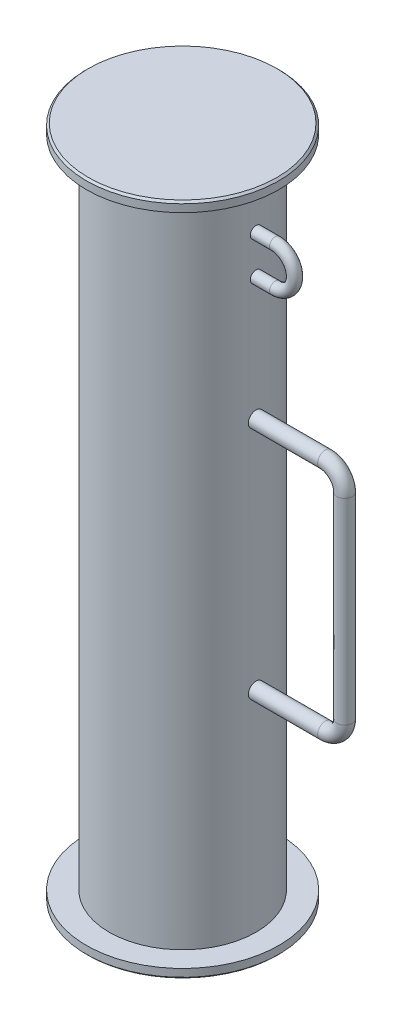
SolidWorks part; units mm, degrees
material "SGP"
ref_plane "前基準面" through (0, 0, 0) normal (0, 0, 1) x (1, 0, 0)
ref_plane "上基準面" through (0, 0, 0) normal (0, 1, 0) x (1, 0, 0)
ref_plane "右基準面" through (0, 0, 0) normal (1, 0, 0) x (0, 0, -1)
sketch "骨架1" plane through (0, 0, 0) normal (0, 1, 0) x (1, 0, 0)
  circle A0 centre (0, 0) radius 38.15
  circle A1 centre (0, 0) radius 50
  circle A2 centre (0, 0) radius 33.95
  dimension "D1" = 100
  dimension "D2" = 76.3
  dimension "D3" = 67.9
sketch "骨架2" plane through (0, 0, 0) normal (0, 0, 1) x (1, 0, 0)
  line L0 (0, 0) -> (0, -398.6797) construction
  point P3 (0, -5)
  point P4 (0, -345)
  point P5 (0, -350)
  dimension "D1" = 5
  dimension "D2" = 340
  dimension "D3" = 5
sketch "草圖1" plane through (0, 0, 0) normal (0, 1, 0) x (1, 0, 0)
  circle A0 centre (0, 0) radius 50
  circle A3 centre (0, 0) radius 50 construction
extrude "填料-伸長1" add sketch "草圖1" against normal up to vertex (5 mm away) up to point (0, -5, 0)
sketch "草圖2" plane through (0, -5, 0) normal (0, -1, 0) x (1, 0, 0)
  circle A0 centre (0, 0) radius 38.15
  circle A1 centre (0, 0) radius 33.95
  circle A2 centre (0, 0) radius 38.15 construction
  circle A3 centre (0, 0) radius 33.95 construction
extrude "填料-伸長2" add sketch "草圖2" along normal up to vertex (340 mm away) up to point (0, -345, 0)
sketch "草圖3" plane through (0, -345, 0) normal (0, -1, 0) x (1, 0, 0)
  circle A0 centre (0, 0) radius 50
  circle A1 centre (0, 0) radius 50 construction
extrude "填料-伸長3" add sketch "草圖3" along normal up to vertex (5 mm away) up to point (0, -350, 0)
ref_plane "平面1" through (38.15, 0, 0) normal (1, 0, 0) x (0, 0, -1)
sketch "草圖4" plane through (38.15, 0, 0) normal (1, 0, 0) x (0, 0, -1)
  line L0 (-50, -350) -> (50, -350) construction
  circle A0 centre (0, -114) radius 4
  dimension "D1" = 8
  dimension "D2" = 236
sketch "草圖5" plane through (0, 0, 0) normal (0, 0, 1) x (1, 0, 0)
  line L0 (38.15, -114) -> (74.15, -114)
  line L1 (38.15, -55) -> (38.15, 55) construction
  line L2 (84.15, -124) -> (84.15, -226)
  line L3 (74.15, -236) -> (38.15, -236)
  line L5 (-50, -350) -> (50, -350) construction
  arc A0 (84.15, -226) -> (74.15, -236) centre (74.15, -226) cw
  arc A1 (74.15, -114) -> (84.15, -124) centre (74.15, -124) cw
  point P10 (84.15, -236)
  point P13 (84.15, -114)
  dimension "D4" = 10
  dimension "D1" = 114
  dimension "D2" = 122
  dimension "D3" = 46
sweep "掃出1" add profiles "草圖4" path "草圖5"
chamfer "導角1" distance 1 angle 45 2 edges at (0, -350, -50) (0, 0, 50)
sketch "草圖6" plane through (38.15, 0, 0) normal (1, 0, 0) x (0, 0, -1)
  line L0 (49, 0) -> (-49, 0) construction
  circle A0 centre (0, -50) radius 3
  dimension "D1" = 6
  dimension "D2" = 50
sketch "草圖7" plane through (0, 0, 0) normal (0, 0, 1) x (1, 0, 0)
  line L0 (38.15, -50) -> (48.15, -50)
  line L1 (38.15, -53) -> (38.15, -47) construction
  line L2 (48.15, -30) -> (38.15, -30)
  line L3 (38.15, -345) -> (38.15, -5) construction
  arc A0 (48.15, -50) -> (48.15, -30) centre (48.15, -40) ccw
  dimension "D2" = 20
  dimension "D1" = 10
  dimension "D4" = 20
sweep "掃出2" add profiles "草圖6" path "草圖7"
